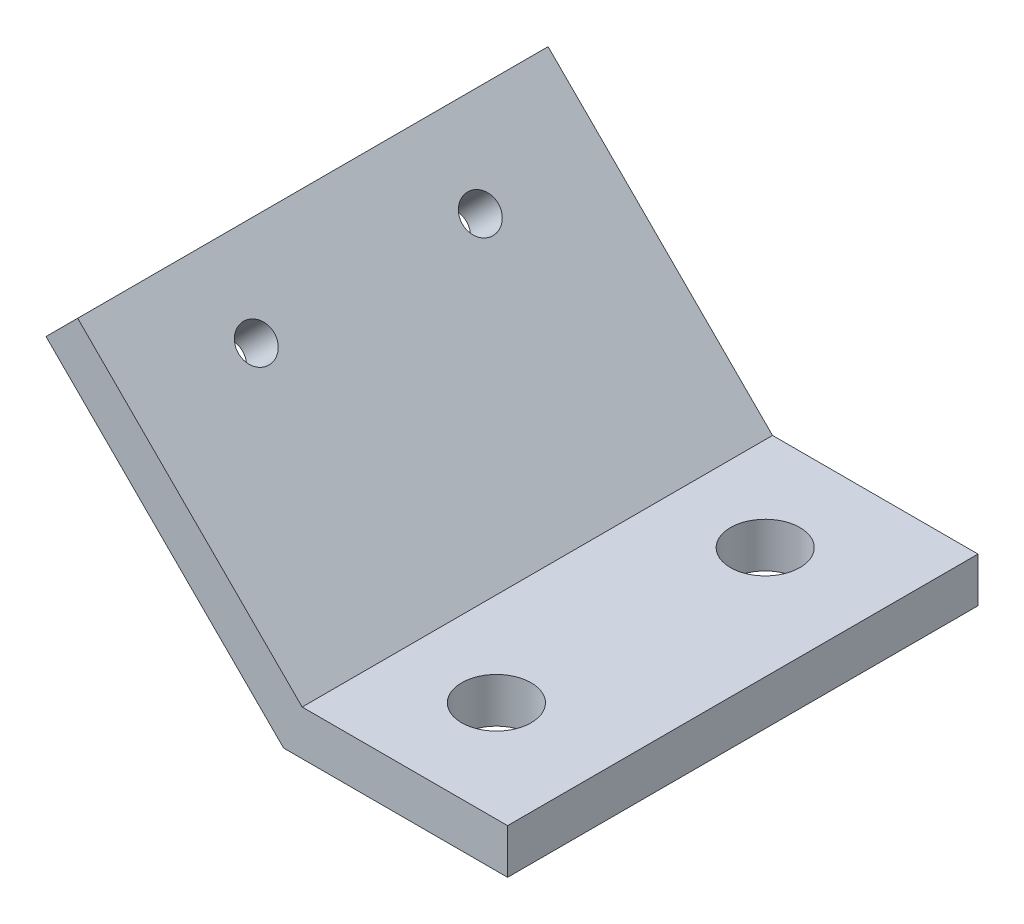
SolidWorks part; units mm, degrees
ref_plane "Front Plane" through (0, 0, 0) normal (0, 0, 1) x (1, 0, 0)
ref_plane "Top Plane" through (0, 0, 0) normal (0, 1, 0) x (1, 0, 0)
ref_plane "Right Plane" through (0, 0, 0) normal (1, 0, 0) x (0, 0, -1)
sketch "Sketch1" plane through (0, 0, 0) normal (0, 0, 1) x (1, 0, 0)
  line L0 (-26.1865, -22.5246) -> (-7.8434, -22.5246)
  line L1 (-7.8434, -22.5246) -> (-7.8434, -26.5246)
  line L2 (-7.8434, -26.5246) -> (-27.8434, -26.5246)
  line L3 (-27.8434, -26.5246) -> (-49.0566, -5.3114)
  line L4 (-49.0566, -5.3114) -> (-46.2282, -2.483)
  line L5 (-46.2282, -2.483) -> (-26.1865, -22.5246)
  dimension "D1" = 90
  dimension "D2" = 135
  dimension "D3" = 4
  dimension "D4" = 4
  dimension "D5" = 30
  dimension "D6" = 20
extrude "Boss-Extrude1" add sketch "Sketch1" along normal blind 42
sketch "Sketch4" plane through (-27.184, -27.184, 0) normal (-0.7071, -0.7071, 0) x (0, 0, 1)
  line L0 (42, 0.9325) -> (0, 0.9325) construction
  line L3 (21, 23.9325) -> (31, 23.9325) construction
  line L4 (21, 23.9325) -> (11, 23.9325) construction
  circle A0 centre (31, 23.9325) radius 1.6
  circle A1 centre (11, 23.9325) radius 1.6
  dimension "D3" = 3.2
  dimension "D4" = 3.2
  dimension "D5" = 23
  dimension "D1" = 10
  dimension "D2" = 10
extrude "Cut-Extrude1" cut sketch "Sketch4" against normal through all and the other way through all
sketch "Sketch5" plane through (0, -26.5246, 0) normal (0, -1, 0) x (1, 0, 0)
  line L0 (-17.8434, 42) -> (-17.8434, 0) construction
  line L1 (-27.8434, 42) -> (-7.8434, 42) construction
  line L2 (-27.8434, 0) -> (-7.8434, 0) construction
  circle A0 centre (-17.8434, 33) radius 3.1
  circle A1 centre (-17.8434, 9) radius 3.1
  point P10 (-17.8434, 21)
  dimension "D1" = 6.2
  dimension "D2" = 6.2
  dimension "D3" = 12
  dimension "D4" = 12
extrude "Cut-Extrude2" cut sketch "Sketch5" against normal through all
